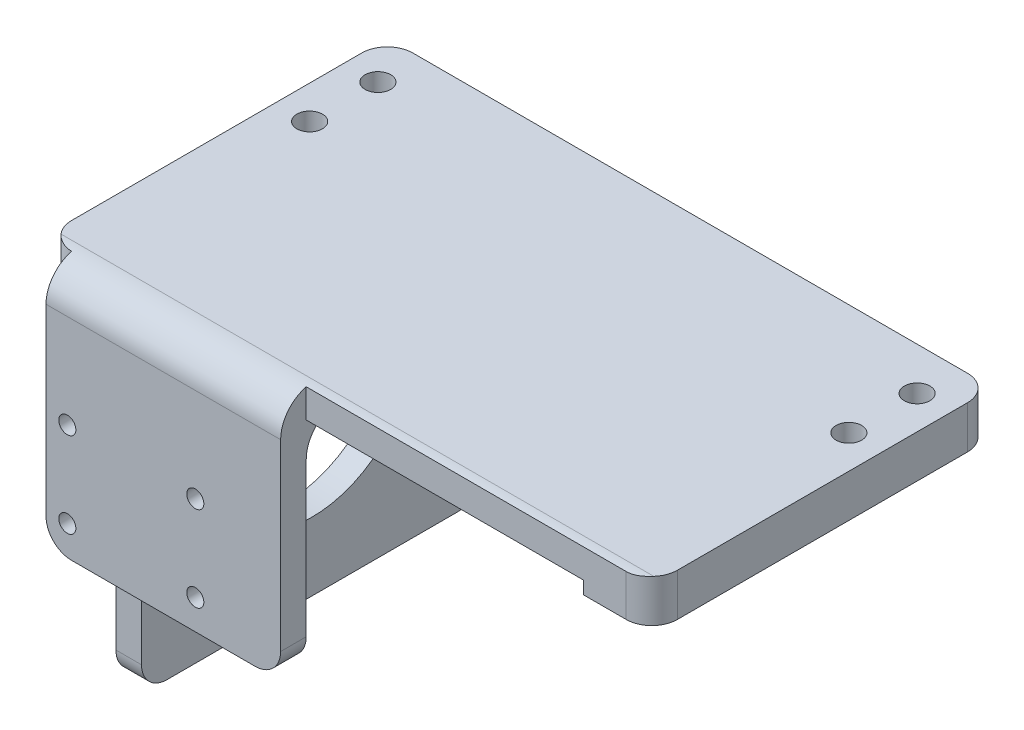
SolidWorks part; units mm, degrees
material "聚脂树脂"
ref_plane "前视基准面" through (0, 0, 0) normal (0, 0, 1) x (1, 0, 0)
ref_plane "上视基准面" through (0, 0, 0) normal (0, 1, 0) x (1, 0, 0)
ref_plane "右视基准面" through (0, 0, 0) normal (1, 0, 0) x (0, 0, -1)
other "Configuration Table"
sketch "草图1" plane through (0, 0, 0) normal (0, 1, 0) x (1, 0, 0)
  line L0 (0, 0) -> (0, 26.3912) construction
  line L1 (-35.5, -20) -> (35.5, -20)
  line L2 (-35.5, -20) -> (-35.5, 20)
  line L3 (-35.5, 20) -> (35.5, 20)
  line L4 (35.5, -20) -> (35.5, 20)
  line L5 (-35.5, -20) -> (35.5, 20) construction
  line L6 (-35.5, 20) -> (35.5, -20) construction
  line L7 (0, 0) -> (47.2738, 0) construction
  line L8 (0, 11) -> (45.2501, 11) construction
  line L10 (-21.5, -20) -> (21.5, -20)
  line L11 (-21.5, -20) -> (-21.5, 20)
  line L12 (-21.5, 20) -> (21.5, 20)
  line L13 (21.5, -20) -> (21.5, 20)
  line L14 (-21.5, -20) -> (21.5, 20) construction
  line L15 (-21.5, 20) -> (21.5, -20) construction
  circle A0 centre (31.6, 15) radius 1.5
  circle A2 centre (31.6, 7) radius 1.5
  circle A3 centre (-31.6, 7) radius 1.5
  circle A4 centre (-31.6, 15) radius 1.5
  point P0 (0, 0)
  dimension "D3" = 3
  dimension "D4" = 8
  dimension "D5" = 63.2
  dimension "D1" = 71
  dimension "D2" = 40
  dimension "D6" = 11
  dimension "D7" = 14
extrude "凸台-拉伸1" add sketch "草图1" along normal blind 5 contours L1 L11 L3 L2 A3 A4 | L13 L1 L4 L3 A0 A2
sketch "草图3" plane through (0, 0, 0) normal (0, -1, 0) x (1, 0, 0)
  line L0 (0, 0) -> (0, -24.947) construction
  line L1 (0, 0) -> (-45.8966, 0) construction
  line L2 (-27.3, 20) -> (-27.3, -20)
  line L4 (-27.3, -20) -> (-24.3, -20)
  line L5 (-24.3, -20) -> (-24.3, 20)
  line L6 (-27.3, 20) -> (-24.3, 20)
  line L7 (-35.5, -20) -> (-21.5, -20) construction
  line L8 (-35.5, 20) -> (-35.5, -20) construction
  point P11 (-24.3, 0)
  point P12 (-27.3, 0)
  dimension "D1" = 3
  dimension "D2" = 8.2
extrude "凸台-拉伸3" add sketch "草图3" along normal blind 36 contours L6 L2 L4 L5
sketch "草图4" plane through (-27.3, 0, 0) normal (-1, 0, 0) x (0, 0, 1)
  line L0 (0, 0) -> (0, -31.6027) construction
  line L1 (0, -16) -> (22.735, -16) construction
  line L3 (20, 0) -> (-20, 0) construction
  circle A0 centre (13, -3) radius 1.5
  circle A1 centre (13, -29) radius 1.5
  circle A2 centre (-13, -29) radius 1.5
  circle A4 centre (0, -16) radius 12
  dimension "D1" = 26
  dimension "D2" = 3
  dimension "D3" = 26
  dimension "D5" = 24
  dimension "D4" = 16
extrude "切除-拉伸1" cut sketch "草图4" against normal blind 30
sketch "草图8" plane through (0, 0, 20) normal (0, 0, 1) x (1, 0, 0)
  line L7 (21.5, 0) -> (-21.5, 0)
  line L10 (21.5, 5) -> (21.5, 0) construction
  line L11 (-21.5, 0) -> (-21.5, 5)
  line L12 (21.5, 5) -> (21.5, 0)
  line L14 (-21.5, 5) -> (21.5, 5)
extrude "凸台-拉伸4" add sketch "草图8" against normal up to surface (40 mm away) up to face at (28.5, 2.5, -20)
sketch "草图9" plane through (0, 0, 0) normal (0, -1, 0) x (1, 0, 0)
  line L0 (-24.3, 20) -> (35.5, 20) construction
  line L1 (-24.3, -20) -> (27.5, -20)
  line L2 (-24.3, -20) -> (-24.3, 20)
  line L3 (-24.3, 20) -> (27.5, 20)
  line L4 (27.5, -20) -> (27.5, 20)
  line L5 (-24.3, -20) -> (27.5, 20) construction
  line L6 (-24.3, 20) -> (27.5, -20) construction
  line L7 (-24.3, -20) -> (-24.3, 20) construction
  line L8 (-24.3, -20) -> (35.5, -20) construction
  line L9 (35.5, 20) -> (35.5, -20) construction
  point P0 (1.6, 0)
  dimension "D1" = 8
extrude "切除-拉伸2" cut sketch "草图9" against normal blind 1.5
fillet "圆角1" radius 3 6 edges at (35.5, 2.5, -20) (35.5, 2.5, 20) (-35.5, 2.5, 20) (-35.5, 2.5, -20) (-25.8, -36, -20) (-25.8, -36, 20)
sketch "草图10" plane through (0, 0, 20) normal (0, 0, 1) x (1, 0, 0)
  line L0 (-32.5, 0) -> (-32.5, 1.5)
  line L1 (-32.5, 5) -> (-32.5, 0) construction
  line L2 (-32.5, 1.5) -> (-5, 1.5)
  line L3 (27.5, 1.5) -> (-24.3, 1.5) construction
  line L4 (-5, 1.5) -> (-5, -23.5)
  line L5 (-5, -23.5) -> (-32.5, -23.5)
  line L6 (-32.5, -23.5) -> (-32.5, 0)
  line L7 (-22.5, -15) -> (7.5949, -15) construction
  line L8 (-22.5, -15) -> (-22.5, 6.5653) construction
  line L9 (-32.5, 1.5) -> (-32.5, 5)
  line L10 (-32.5, 5) -> (-5, 5)
  line L11 (-32.5, 5) -> (32.5, 5) construction
  line L12 (-5, 5) -> (-5, 1.5)
  circle A0 centre (-15, -10) radius 1
  circle A1 centre (-15, -20) radius 1
  circle A2 centre (-30, -20) radius 1
  circle A3 centre (-30, -10) radius 1
  line M13 (32.5, 5) -> (-32.5, 5)
  line M14 (-32.5, 5) -> (-32.5, 0)
  line M15 (-32.5, 0) -> (-27.3, 0)
  line M16 (-27.3, 0) -> (-27.3, -33)
  line M18 (-24.3, -33) -> (-24.3, 1.5)
  line M19 (-24.3, 1.5) -> (27.5, 1.5)
  dimension "D2" = 2
  dimension "D3" = 15
  dimension "D4" = 10
  dimension "D1" = 5
  dimension "D5" = 15
  dimension "D6" = 25
  dimension "D7" = 22.5
extrude "凸台-拉伸5" add sketch "草图10" along normal blind 3 contours L12 L2 M13 M14 M19 | L5 L4 A0 A1 M19 M18 | L5 L2 M18 M14 M15 M16 | L6 L5 A2 A3 M16 M15
sketch "草图11" plane through (0, 0, 20) normal (0, 0, -1) x (-1, 0, 0)
  circle A0 centre (15, -10) radius 2.5
  circle A1 centre (30, -10) radius 2
  circle A2 centre (30, -20) radius 2
  circle A3 centre (15, -20) radius 2.5
  dimension "D1" = 5
  dimension "D2" = 5
  dimension "D3" = 4
  dimension "D4" = 4
extrude "切除-拉伸3" cut sketch "草图11" against normal blind 1
fillet "圆角2" radius 4 2 edges at (-14.65, 1.5, 20) (-18.75, 5, 23)
fillet "圆角3" radius 3 2 edges at (-32.5, -23.5, 21.5) (-5, -23.5, 21.5)
